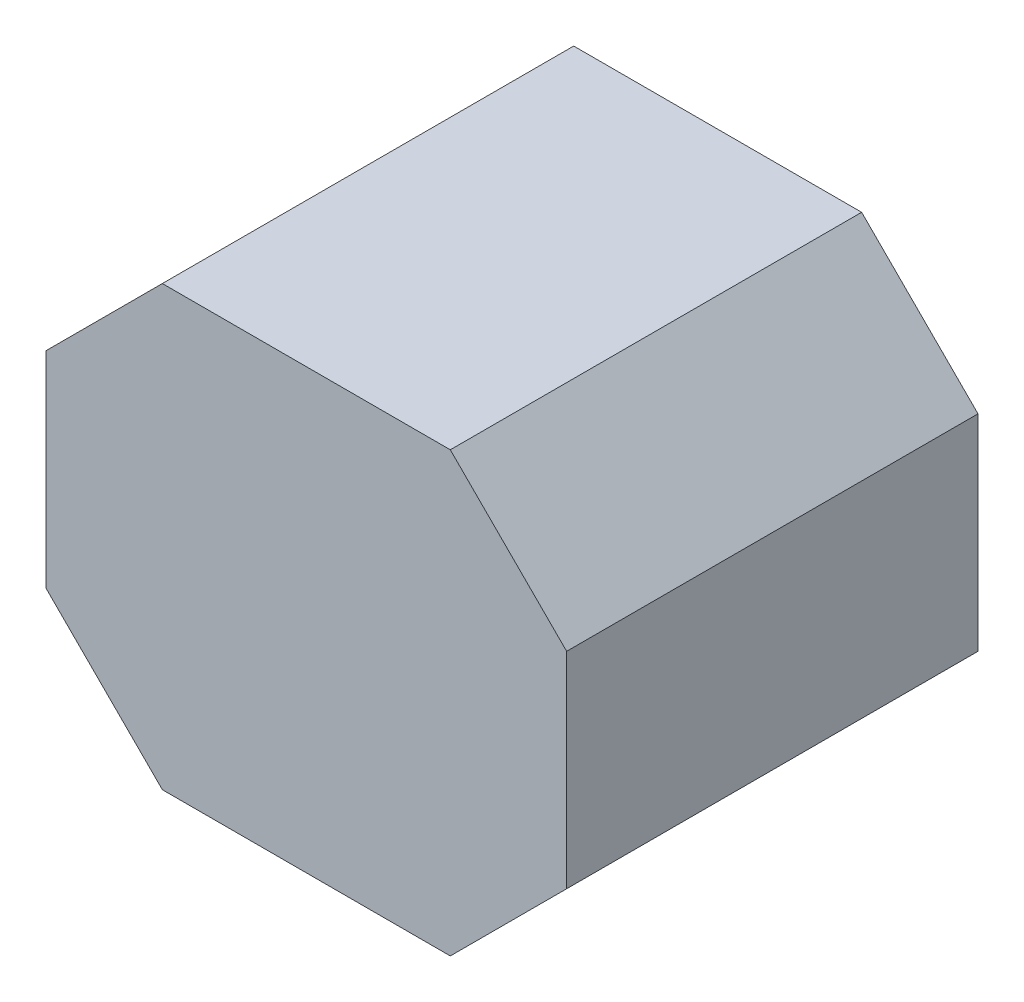
SolidWorks part; units mm, degrees
ref_plane "Front Plane" through (0, 0, 0) normal (0, 0, 1) x (1, 0, 0)
ref_plane "Top Plane" through (0, 0, 0) normal (0, 1, 0) x (1, 0, 0)
ref_plane "Right Plane" through (0, 0, 0) normal (1, 0, 0) x (0, 0, -1)
sketch "Sketch1" plane through (0, 0, 0) normal (0, 0, 1) x (1, 0, 0)
  line L0 (-88.9, 0) -> (88.9, 0)
  line L1 (-88.9, 0) -> (-160.742, 71.842)
  line L2 (-160.742, 71.842) -> (-160.742, 198.842)
  line L3 (-273.7569, 135.342) -> (180.7801, 135.342) construction
  line L4 (0, 184.2646) -> (0, -72.8795) construction
  line L5 (88.9, 0) -> (160.742, 71.842)
  line L6 (160.742, 71.842) -> (160.742, 198.842)
  line L7 (88.9, 270.6841) -> (160.742, 198.842)
  line L8 (-88.9, 270.6841) -> (-160.742, 198.842)
  line L9 (-88.9, 270.6841) -> (88.9, 270.6841)
  point P13 (-160.742, 135.342)
  point P14 (160.742, 135.342)
  point P17 (0, 0)
  dimension "D1" = 177.8
  dimension "D2" = 101.6
  dimension "D3" = 63.5
  dimension "D4" = 135
extrude "Boss-Extrude1" add sketch "Sketch1" along normal mid plane 254
